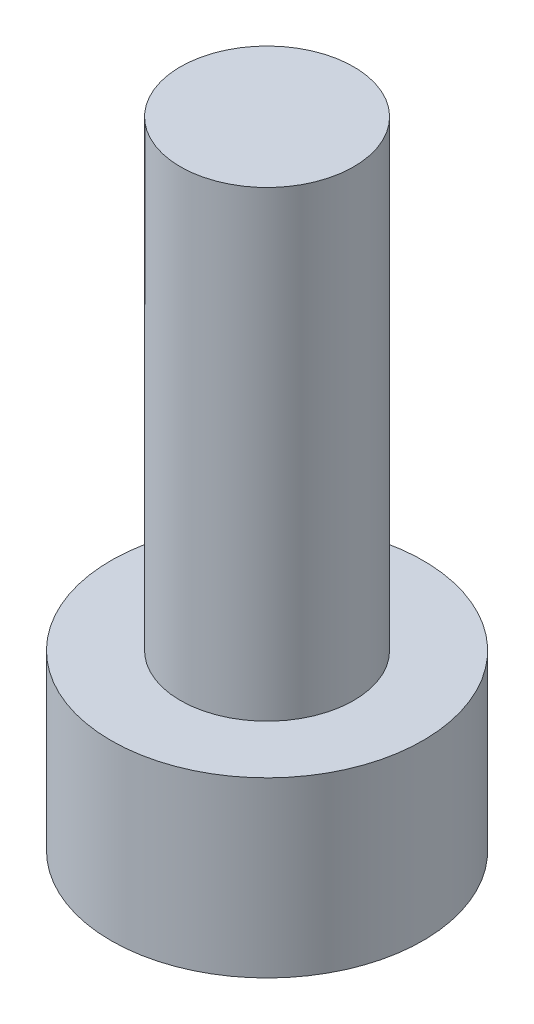
SolidWorks part; units mm, degrees
material "Alloy Steel"
ref_plane "Front Plane" through (0, 0, 0) normal (0, 0, 1) x (1, 0, 0)
ref_plane "Top Plane" through (0, 0, 0) normal (0, 1, 0) x (1, 0, 0)
ref_plane "Right Plane" through (0, 0, 0) normal (1, 0, 0) x (0, 0, -1)
sketch "Sketch1" plane through (0, 0, 0) normal (0, 1, 0) x (1, 0, 0)
  circle A0 centre (0, 0) radius 2.7
  dimension "D1" = 5.4
extrude "Boss-Extrude1" add sketch "Sketch1" along normal blind 3
sketch "Sketch3" plane through (0, 3, 0) normal (0, 1, 0) x (1, 0, 0)
  circle A0 centre (0, 0) radius 1.5
  dimension "D1" = 3
extrude "Boss-Extrude2" add sketch "Sketch3" along normal blind 8
